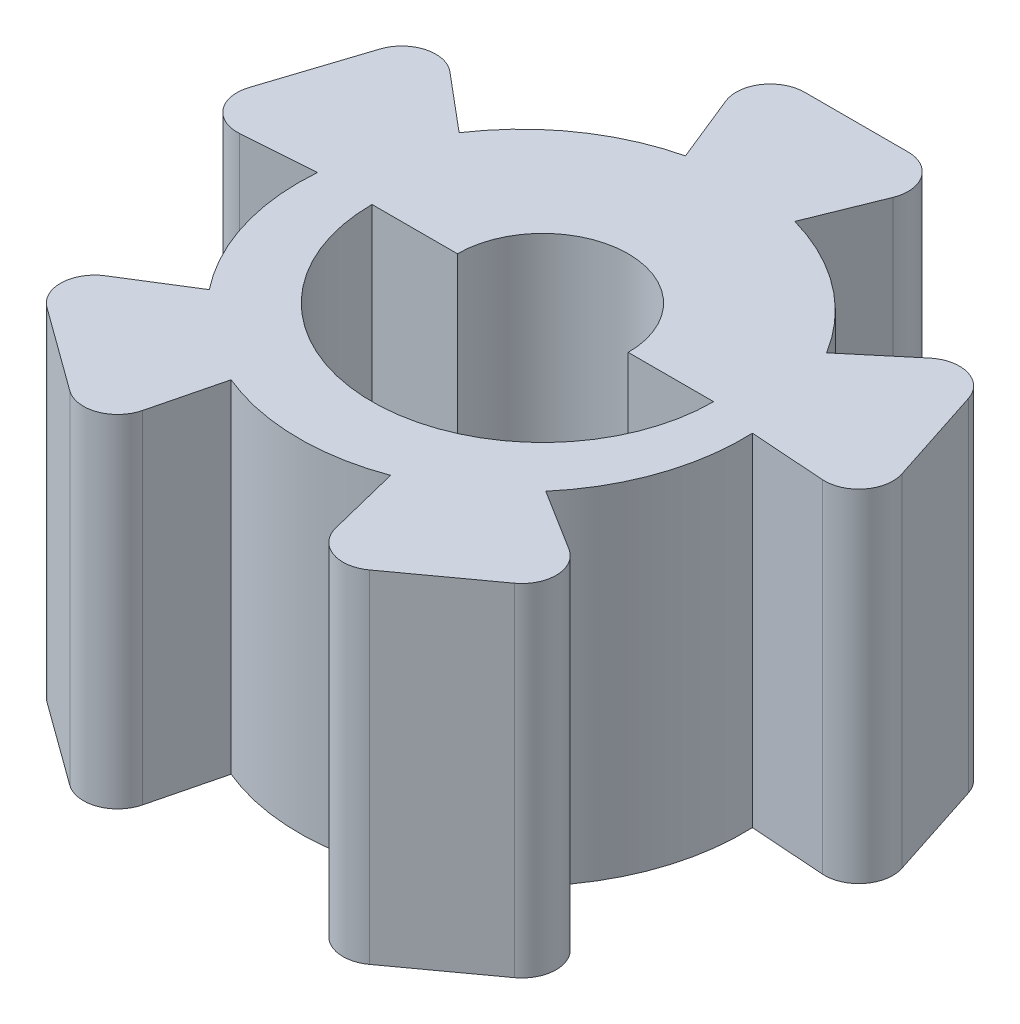
SolidWorks part; units mm, degrees
ref_plane "Front Plane" through (0, 0, 0) normal (0, 0, 1) x (1, 0, 0)
ref_plane "Top Plane" through (0, 0, 0) normal (0, 1, 0) x (1, 0, 0)
ref_plane "Right Plane" through (0, 0, 0) normal (1, 0, 0) x (0, 0, -1)
sketch "Sketch1" plane through (0, 0, 0) normal (0, 1, 0) x (1, 0, 0)
  line L0 (-1.5, 4.5881) -> (-0.8216, 2.909)
  line L1 (-1.5, 4.5881) -> (1.5, 4.5881)
  line L5 (4.0949, 2.6095) -> (2.7076, 1.4455)
  line L6 (4.0949, 2.6095) -> (5.0219, -0.2436)
  line L7 (1.5, 4.5881) -> (0.8094, 2.8789)
  line L8 (5.0219, -0.2436) -> (3.1829, -0.115)
  line L9 (3.9421, -3.3229) -> (2.4063, -2.3632)
  line L10 (3.9421, -3.3229) -> (1.515, -5.0863)
  line L11 (1.515, -5.0863) -> (1.069, -3.2975)
  line L12 (-1.7473, -5.0108) -> (-1.3091, -3.2536)
  line L13 (-1.7473, -5.0108) -> (-4.1743, -3.2475)
  line L14 (-4.1743, -3.2475) -> (-2.6109, -2.2706)
  line L15 (-5.1106, -0.1215) -> (-3.3041, 0.0048)
  line L16 (-5.1106, -0.1215) -> (-4.1836, 2.7316)
  line L17 (-4.1836, 2.7316) -> (-2.7714, 1.5467)
  arc A2 (-3.3041, 0.0048) -> (-2.6109, -2.2706) centre (-0.0642, -0.2515) ccw
  arc A3 (-1.3091, -3.2536) -> (1.069, -3.2975) centre (-0.0642, -0.2515) ccw
  arc A4 (-0.8216, 2.909) -> (-2.7714, 1.5467) centre (-0.0642, -0.2515) ccw
  arc A5 (2.7076, 1.4455) -> (0.8094, 2.8789) centre (-0.0642, -0.2515) ccw
  arc A6 (2.4063, -2.3632) -> (3.1829, -0.115) centre (-0.0642, -0.2515) ccw
  point P1 (0, 2.9889)
  point P2 (0, 0)
  point P6 (0, 0)
  point P26 (0, 0)
  point P27 (-0.0642, -0.2515)
  dimension "D1" = 292
  dimension "D2" = 292
  dimension "D3" = 5
  dimension "D4" = 6.5
extrude "Boss-Extrude1" add sketch "Sketch1" along normal blind 5
sketch "Sketch2" plane through (0, 5, 0) normal (0, 1, 0) x (1, 0, 0)
  line L0 (-2.5, 0) -> (-1.25, 0)
  line L1 (1.25, 0) -> (2.5, 0)
  circle A0 centre (0, 0) radius 2.5
  arc A1 (1.25, 0) -> (-1.25, 0) centre (0, 0) ccw
  dimension "D1" = 5
  dimension "D2" = 2.5
extrude "Cut-Extrude1" cut sketch "Sketch2" against normal blind 10 contours L1 A1 L0 A0
fillet "Fillet1" radius 0.5 10 edges at (-1.5, 2.5, -4.5881) (1.5, 2.5, -4.5881) (4.0949, 2.5, -2.6095) (5.0219, 2.5, 0.2436) (3.9421, 2.5, 3.3229) (1.515, 2.5, 5.0863) (-1.7473, 2.5, 5.0108) (-4.1743, 2.5, 3.2475) (-5.1106, 2.5, 0.1215) (-4.1836, 2.5, -2.7316)
